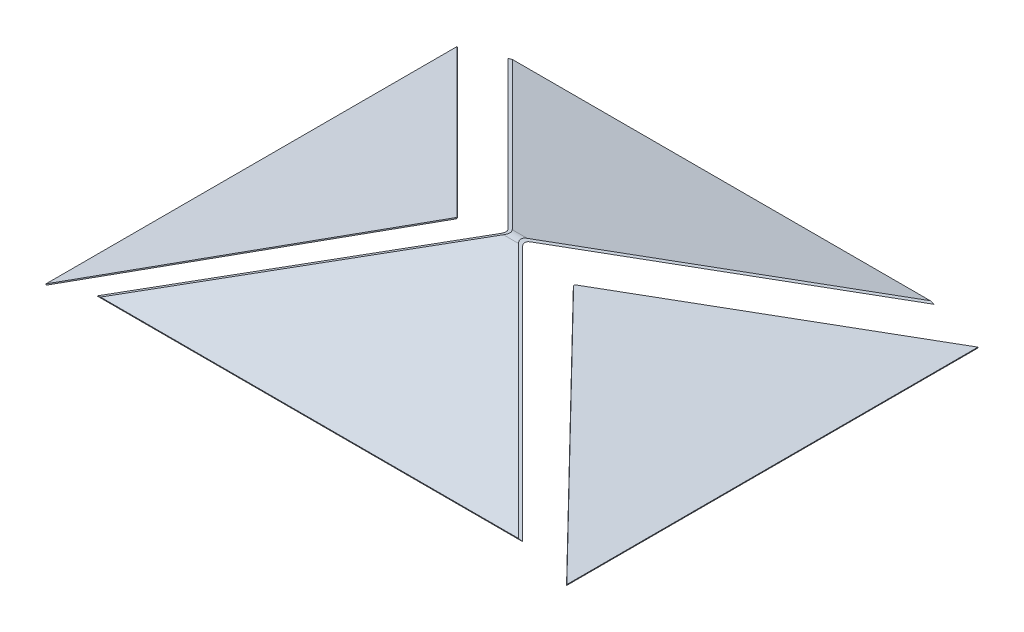
SolidWorks part; units mm, degrees
ref_plane "Front Plane" through (0, 0, 0) normal (0, 0, 1) x (1, 0, 0)
ref_plane "Top Plane" through (0, 0, 0) normal (0, 1, 0) x (1, 0, 0)
ref_plane "Right Plane" through (0, 0, 0) normal (1, 0, 0) x (0, 0, -1)
ref_plane "Plane1"
sketch "Sketch1" plane through (0, 0, 0) normal (1, 0, 0) x (0, 1, 0)
  line L0 (-51.7638, 193.1852) -> (-1.0403, 3.8823)
  line L1 (-1.0403, -3.8823) -> (-51.7638, -193.1852)
  line L2 (-51.7638, -193.1852) -> (-50.7979, -193.444)
  line L3 (-50.7979, -193.444) -> (-0.0743, -4.1411)
  line L4 (-0.0743, 4.1411) -> (-50.7979, 193.444)
  line L5 (-50.7979, 193.444) -> (-51.7638, 193.1852)
  arc A0 (-1.0403, -3.8823) -> (-1.0403, 3.8823) centre (-15.5291, 0) ccw
  arc A1 (-0.0743, -4.1411) -> (-0.0743, 4.1411) centre (-15.5291, 0) ccw
  dimension "D3" = 15
  dimension "D1" = 200
  dimension "D2" = 200
  dimension "D4" = 90
extrude "Extrusion7" add sketch "Sketch1" along normal blind 400
ref_plane "Plane2"
sketch "Sketch2" plane through (0, 0, 0) normal (0, 0, 1) x (1, 0, 0)
  line L0 (0, -51.7638) -> (196.1177, 0.7858)
  line L1 (203.8823, 0.7858) -> (400, -51.7638)
  line L2 (400, -51.7638) -> (400, 8.2362)
  line L3 (400, 8.2362) -> (0, 8.2362)
  line L4 (0, 8.2362) -> (0, -51.7638)
  line L5 (400, -51.7638) -> (0, -51.7638) construction
  arc A0 (203.8823, 0.7858) -> (196.1177, 0.7858) centre (200, -13.7031) ccw
  dimension "D2" = 15
  dimension "D1" = 15
  dimension "D3" = 60
extrude "Extrusion8" cut sketch "Sketch2" against normal through all and the other way through all
sketch "Sketch3" plane through (13.854, 51.7037, 0) normal (0.2588, 0.9659, 0) x (-0.9659, 0.2588, 0)
  line L0 (-445.7725, 196.3756) -> (-445.7725, -189.9947)
  line L1 (-445.7725, -189.9947) -> (-249.7918, -0.6918)
  line L2 (-249.7918, 0.6918) -> (-445.7725, 196.3756)
  ellipse E0 centre (-259.7678, 0) end of major axis (-269.7678, 0) minor radius 10 (-249.7918, -0.6918) -> (-249.7918, 0.6918) ccw
extrude "Extrusion9" add sketch "Sketch3" along normal blind 1
sketch "Sketch4" plane through (12.941, -48.2963, 0) normal (-0.2588, 0.9659, 0) x (-0.9659, -0.2588, 0)
  line L0 (-136.5786, -0.6918) -> (59.4022, -189.9947)
  line L1 (59.4022, -189.9947) -> (59.4022, 196.3756)
  line L2 (59.4022, 196.3756) -> (-136.5786, 0.6918)
  ellipse E0 centre (-126.6025, 0) end of major axis (-126.6025, 10) minor radius 10 (-136.5786, 0.6918) -> (-136.5786, -0.6918) ccw
extrude "Extrusion10" add sketch "Sketch4" along normal blind 1
